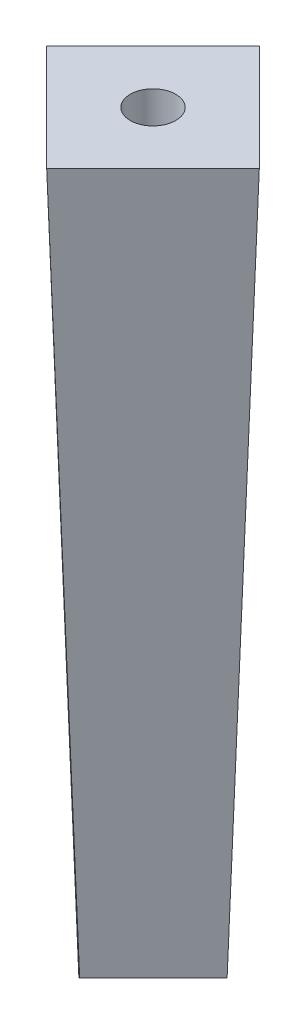
SolidWorks part; units mm, degrees
ref_plane "Front Plane" through (0, 0, 0) normal (0, 0, 1) x (1, 0, 0)
ref_plane "Top Plane" through (0, 0, 0) normal (0, 1, 0) x (1, 0, 0)
ref_plane "Right Plane" through (0, 0, 0) normal (1, 0, 0) x (0, 0, -1)
sketch "Sketch1" plane through (0, 0, 0) normal (0, 0, 1) x (1, 0, 0)
  line L0 (75.9361, 50.1301) -> (91.348, 50.1301)
  line L1 (91.348, 50.1301) -> (91.348, 200.0187)
  line L2 (91.348, 200.0187) -> (69.123, 200.0187)
  line L3 (69.123, 200.0187) -> (75.9361, 50.1301)
  dimension "D1" = 22.225
extrude "Boss-Extrude1" add sketch "Sketch1" along normal blind 22.225 contours L1 L2 L3 L0
sketch "Sketch3" plane through (91.348, 0, 0) normal (1, 0, 0) x (0, 0, -1)
  line L0 (-22.225, 50.1301) -> (0, 50.1301) construction
  point P0 (-15.494, 50.1301)
  dimension "D1" = 15.494
ref_plane "Plane1" through (39.0133, 1.752, -39.0133) normal (-0.7068, -0.0317, 0.7068) x (0.706, 0.0317, 0.7075)
sketch "Sketch4" plane through (39.0133, 1.752, -39.0133) normal (-0.7068, -0.0317, 0.7068) x (0.706, 0.0317, 0.7075)
  line L1 (46.8753, 206.4803) -> (89.7709, 206.4803)
  line L2 (46.8753, 206.4803) -> (46.8753, 39.9573)
  line L3 (46.8753, 39.9573) -> (89.7709, 39.9573)
  line L4 (89.7709, 206.4803) -> (89.7709, 39.9573)
extrude "Cut-Extrude2" cut sketch "Sketch4" along normal blind 22.225
pattern_circular "CirPattern1" count 4 over 360 about axis through (91.348, 0, 0) along (0, 1, 0) of "Boss-Extrude1", "Cut-Extrude2"
sketch "Sketch5" plane through (0, 200.0187, 0) normal (0, 1, 0) x (1, 0, 0)
  circle A0 centre (91.348, 0) radius 4.7625
  dimension "D1" = 9.525
extrude "Cut-Extrude3" cut sketch "Sketch5" against normal through all
